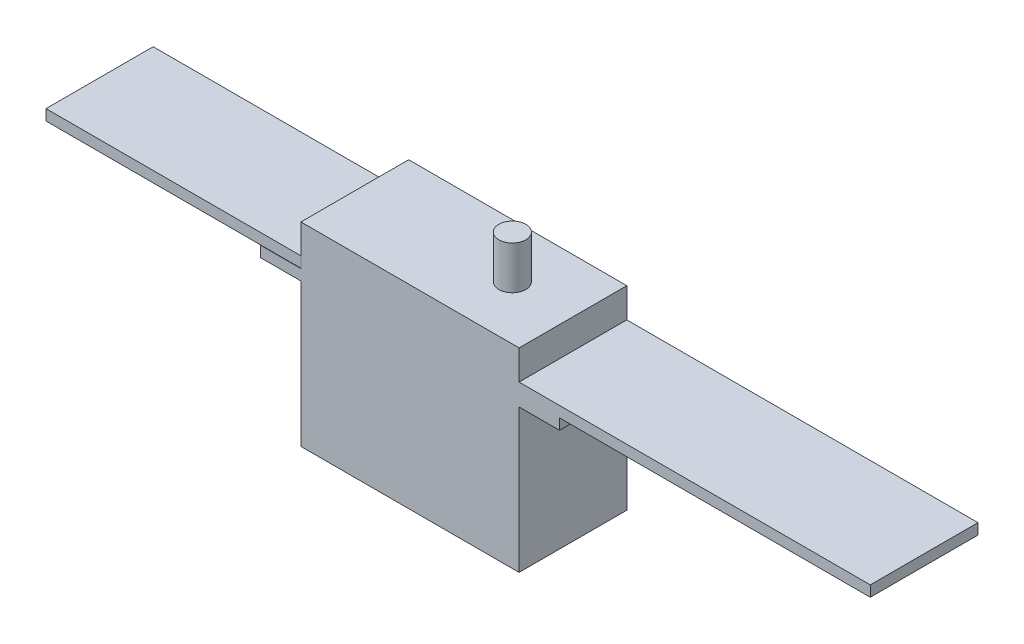
SolidWorks part; units mm, degrees
material "Plain Carbon Steel"
ref_plane "Front Plane" through (0, 0, 0) normal (0, 0, 1) x (1, 0, 0)
ref_plane "Top Plane" through (0, 0, 0) normal (0, 1, 0) x (1, 0, 0)
ref_plane "Right Plane" through (0, 0, 0) normal (1, 0, 0) x (0, 0, -1)
sketch "Sketch1" plane through (0, 0, 0) normal (0, 1, 0) x (1, 0, 0)
  line L1 (-16.7433, 10.7539) -> (23.7567, 10.7539)
  line L2 (-16.7433, 10.7539) -> (-16.7433, -9.2461)
  line L3 (-16.7433, -9.2461) -> (23.7567, -9.2461)
  line L4 (23.7567, 10.7539) -> (23.7567, -9.2461)
  dimension "D1" = 40.5
  dimension "D2" = 20
extrude "Boss-Extrude1" add sketch "Sketch1" along normal blind 36.1
sketch "Sketch2" plane through (0, 36.1, 0) normal (0, 1, 0) x (1, 0, 0)
  line L0 (23.7567, 10.7539) -> (-16.7433, 10.7539) construction
  line L1 (23.7567, -9.2461) -> (23.7567, 10.7539) construction
  circle A0 centre (12.5067, 0.7539) radius 2.5
  dimension "D1" = 10
  dimension "D2" = 11.25
extrude "Boss-Extrude2" add sketch "Sketch2" along normal blind 8
sketch "Sketch3" plane through (-16.7433, 0, 0) normal (-1, 0, 0) x (0, 0, 1)
  line L0 (-10.7539, 36.1) -> (-10.7539, 0) construction
  line L1 (-10.7539, 28.6) -> (9.2461, 28.6)
  line L2 (-10.7539, 28.6) -> (-10.7539, 26.6)
  line L3 (-10.7539, 26.6) -> (9.2461, 26.6)
  line L4 (9.2461, 28.6) -> (9.2461, 26.6)
  line L5 (9.2461, 36.1) -> (9.2461, 0) construction
  line L6 (-10.7539, 0) -> (9.2461, 0) construction
  dimension "D1" = 26.6
  dimension "D2" = 2
extrude "Boss-Extrude3" add sketch "Sketch3" along normal blind 7.5 and the other way blind 48
sketch "Sketch4" plane through (0, 28.6, 0) normal (0, 1, 0) x (1, 0, 0)
  line L0 (23.7567, 10.7539) -> (-16.7433, 10.7539) construction
  line L1 (-16.7433, -9.2461) -> (23.7567, -9.2461) construction
  line L2 (-16.7433, 10.7539) -> (-24.2433, 10.7539) construction
  line L3 (31.2567, 10.7539) -> (23.7567, 10.7539) construction
  circle A0 centre (-20.4933, 5.7539) radius 2
  circle A1 centre (27.5067, 5.7539) radius 2
  circle A2 centre (-20.4933, -4.2461) radius 2
  circle A3 centre (27.5067, -4.2461) radius 2
  point P8 (3.5067, 10.7539)
  point P11 (3.5067, -9.2461)
  point P14 (3.5067, -9.2461)
  point P15 (3.5067, 10.7539)
  point P16 (-20.4933, 10.7539)
  dimension "D1" = 24
  dimension "D2" = 24
  dimension "D3" = 24
  dimension "D4" = 24
  dimension "D5" = 10
  dimension "D6" = 10
  dimension "D7" = 5
  dimension "D8" = 5
extrude "Cut-Extrude1" cut sketch "Sketch4" against normal blind 7.5
sketch "Sketch5" plane through (0, 28.6, 0) normal (0, 1, 0) x (1, 0, 0)
  line L0 (-16.7433, 10.7539) -> (-16.7433, -9.2461) construction
  line L1 (-16.7433, -9.1894) -> (-64.1266, -9.1894)
  line L2 (-16.7433, -9.1894) -> (-16.7433, 10.7107)
  line L3 (-16.7433, 10.7107) -> (-64.1266, 10.7107)
  line L4 (-64.1266, -9.1894) -> (-64.1266, 10.7107)
  line L5 (23.7567, -9.2461) -> (23.7567, 10.7539) construction
  line L6 (23.7567, -9.2461) -> (88.9534, -9.2461)
  line L7 (23.7567, -9.2461) -> (23.7567, 10.7535)
  line L8 (23.7567, 10.7535) -> (88.9534, 10.7535)
  line L9 (88.9534, -9.2461) -> (88.9534, 10.7535)
extrude "Boss-Extrude4" add sketch "Sketch5" along normal blind 2
